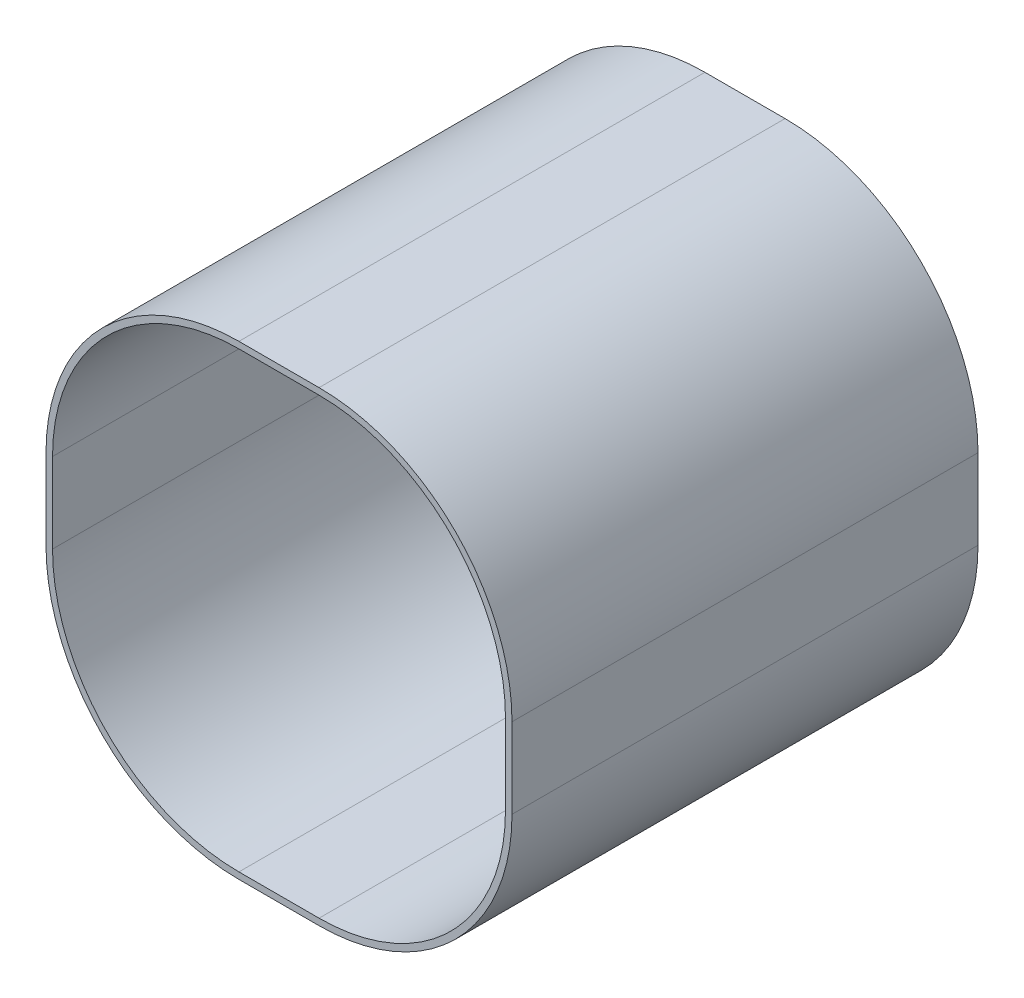
SolidWorks part; units mm, degrees
ref_plane "Front Plane" through (0, 0, 0) normal (0, 0, 1) x (1, 0, 0)
ref_plane "Top Plane" through (0, 0, 0) normal (0, 1, 0) x (1, 0, 0)
ref_plane "Right Plane" through (0, 0, 0) normal (1, 0, 0) x (0, 0, -1)
sketch "Sketch1" plane through (0, 0, 0) normal (0, 0, 1) x (1, 0, 0)
  line L1 (-12.15, 12.15) -> (12.15, 12.15)
  line L2 (-12.15, 12.15) -> (-12.15, -12.15)
  line L3 (-12.15, -12.15) -> (12.15, -12.15)
  line L4 (12.15, 12.15) -> (12.15, -12.15)
  line L5 (-12.15, 12.15) -> (12.15, -12.15) construction
  line L6 (-12.15, -12.15) -> (12.15, 12.15) construction
  line L7 (-12.5, 12.5) -> (12.5, 12.5)
  line L8 (-12.5, 12.5) -> (-12.5, -12.5)
  line L9 (-12.5, -12.5) -> (12.5, -12.5)
  line L10 (12.5, 12.5) -> (12.5, -12.5)
  line L11 (-12.5, 12.5) -> (12.5, -12.5) construction
  line L12 (-12.5, -12.5) -> (12.5, 12.5) construction
  point P0 (0, 0)
  point P7 (0, 0)
  dimension "D1" = 0.35
  dimension "D2" = 0.35
  dimension "D3" = 25
extrude "Boss-Extrude1" add sketch "Sketch1" along normal blind 25
fillet "Fillet1" [suppressed] radius 2
fillet "Fillet2" [suppressed] radius 2.4
fillet "Fillet3" radius 10 4 edges at (12.15, -12.15, 12.5) (12.15, 12.15, 12.5) (-12.15, 12.15, 12.5) (-12.15, -12.15, 12.5)
fillet "Fillet4" radius 10.35 4 edges at (12.5, 12.5, 12.5) (12.5, -12.5, 12.5) (-12.5, -12.5, 12.5) (-12.5, 12.5, 12.5)
